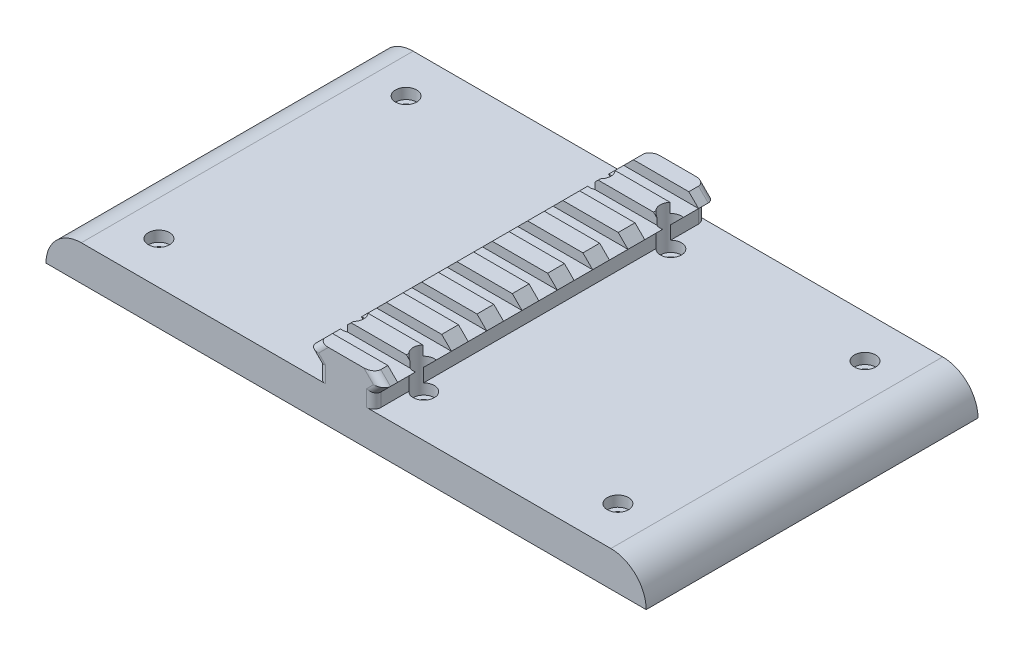
SolidWorks part; units mm, degrees
ref_plane "前视基准面" through (0, 0, 0) normal (0, 0, 1) x (1, 0, 0)
ref_plane "上视基准面" through (0, 0, 0) normal (0, 1, 0) x (1, 0, 0)
ref_plane "右视基准面" through (0, 0, 0) normal (1, 0, 0) x (0, 0, -1)
sketch "草图2" plane through (0, 0, 0) normal (0, 0, 1) x (1, 0, 0)
  line L0 (7.84, 9.32) -> (10.6, 6.56)
  line L1 (7.84, 9.32) -> (-7.84, 9.32)
  line L2 (-7.84, 9.32) -> (-10.6, 6.56)
  line L3 (-10.6, 6.56) -> (-7.84, 3.8)
  line L4 (-7.84, 3.8) -> (-7.84, 0)
  line L5 (-7.84, 0) -> (7.84, 0)
  line L6 (10.6, 6.56) -> (7.84, 3.8)
  line L7 (7.84, 3.8) -> (7.84, 0)
  point P4 (0, 0)
  dimension "D1" = 3.8
  dimension "D2" = 5.52
  dimension "D3" = 21.2
  dimension "D4" = 90
sketch "草图3" plane through (0, 0, 0) normal (0, 0, 1) x (1, 0, 0)
  line L0 (-7.84, 0) -> (7.84, 0) construction
  line L1 (-75, 0) -> (75, 0)
  line L3 (-75, -10) -> (75, -10)
  line L5 (-85, -10) -> (-75, -10)
  line L6 (-85, -10) -> (-75, -10)
  line L7 (0, 0) -> (0, -10) construction
  line L8 (85, -10) -> (75, -10)
  line L9 (85, -10) -> (75, -10)
  line L10 (-75, -10) -> (75, -10)
  arc A0 (-75, 0) -> (-85, -10) centre (-75, -10) ccw
  arc A1 (75, 0) -> (85, -10) centre (75, -10) cw
  point P9 (0, 0)
  point P16 (0, -10)
  dimension "D1" = 75
  dimension "D2" = 10
extrude "凸台-拉伸1" add sketch "草图3" along normal blind 94 contours L7 L1 A0 L5 L3 | L1 L7 L10 L8 A1
extrude "凸台-拉伸2" add sketch "草图2" along normal through all
sketch "草图4" plane through (0, 0, 0) normal (0, 1, 0) x (1, 0, 0)
  line L0 (0, -47) -> (44.5473, -47) construction
  line L1 (0, 0) -> (0, -45.4367) construction
  line L2 (-75, -94) -> (-75, 0) construction
  circle A0 centre (-65, -12) radius 1.5
  circle A1 centre (-10, -12) radius 1.5
  circle A2 centre (10, -12) radius 1.5
  circle A3 centre (65, -12) radius 1.5
  circle A4 centre (65, -82) radius 1.5
  circle A5 centre (10, -82) radius 1.5
  circle A6 centre (-65, -82) radius 1.5
  circle A7 centre (-10, -82) radius 1.5
  point P12 (-75, -47)
  dimension "D1" = 3
  dimension "D2" = 55
  dimension "D3" = 10
  dimension "D4" = 35
extrude "切除-拉伸1" cut sketch "草图4" against normal through all
sketch "草图5" plane through (0, 0, 0) normal (0, 1, 0) x (1, 0, 0)
  line L0 (0, 0) -> (0, 18.7044) construction
  line L1 (-117.8018, -47) -> (-101.1049, -47) construction
  line L2 (-75, -94) -> (-75, 0) construction
  circle A0 centre (-65, -12) radius 3
  circle A3 centre (-10, -12) radius 3
  circle A4 centre (10, -12) radius 3
  circle A5 centre (65, -12) radius 3
  circle A6 centre (65, -82) radius 3
  circle A7 centre (10, -82) radius 3
  circle A8 centre (-10, -82) radius 3
  circle A9 centre (-65, -82) radius 3
  point P14 (-75, -47)
  dimension "D1" = 6
extrude "切除-拉伸2" cut sketch "草图5" along normal through all from offset 3 offset against normal yes
sketch "草图6" plane through (0, 9.32, 0) normal (0, 1, 0) x (1, 0, 0)
  line L0 (-10.6, -9.0606) -> (-10.6, 0) construction
  line L1 (-10.6, -4.75) -> (10.6, -4.75)
  line L2 (-10.6, -4.75) -> (-10.6, -10)
  line L3 (-10.6, -10) -> (10.6, -10)
  line L4 (10.6, -4.75) -> (10.6, -10)
  line L5 (10.6, -9.0606) -> (10.6, 0) construction
  line L6 (7.84, 0) -> (-7.84, 0) construction
  dimension "D1" = 5.25
  dimension "D2" = 4.75
extrude "切除-拉伸3" cut sketch "草图6" against normal blind 2.76
pattern_linear "阵列(线性)1" count 9 spacing 10 along (0, 0, 1) of "切除-拉伸3"
fillet "圆角2" radius 2 12 edges at (9.22, 7.94, 94) (9.22, 7.94, 0) (9.22, 5.18, 94) (9.22, 5.18, 0) (-9.22, 5.18, 94) (-9.22, 5.18, 0) (-9.22, 7.94, 94) (-9.22, 7.94, 0) (-7.84, 1.9, 94) (-7.84, 1.9, 0) (7.84, 1.9, 94) (7.84, 1.9, 0)
